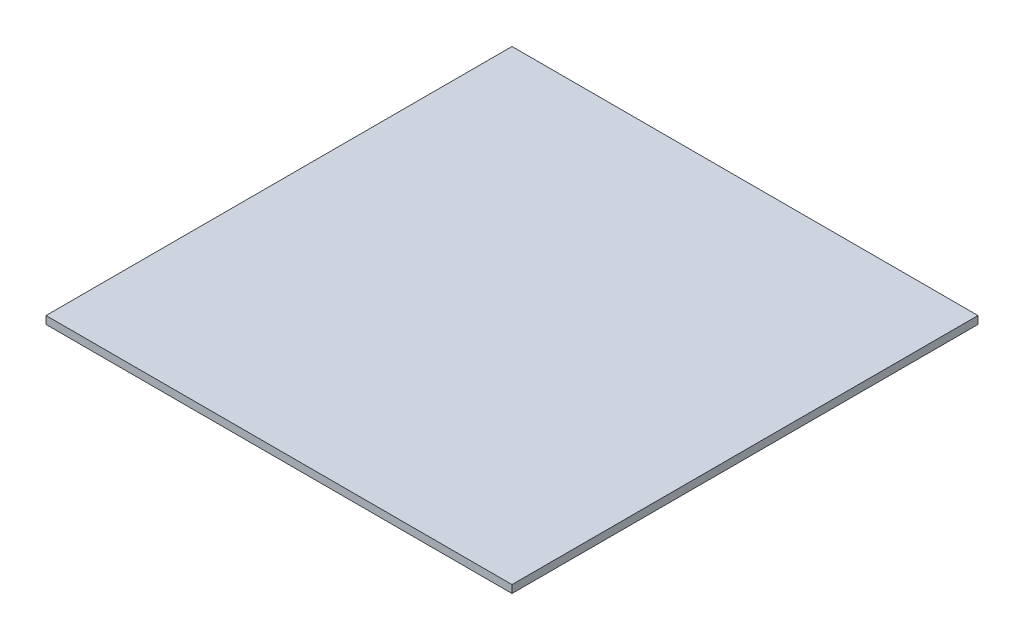
SolidWorks part; units mm, degrees
ref_plane "Front Plane" through (0, 0, 0) normal (0, 0, 1) x (1, 0, 0)
ref_plane "Top Plane" through (0, 0, 0) normal (0, 1, 0) x (1, 0, 0)
ref_plane "Right Plane" through (0, 0, 0) normal (1, 0, 0) x (0, 0, -1)
sketch "Sketch1" plane through (0, 0, 0) normal (0, 1, 0) x (1, 0, 0)
  line L1 (-152.4, -152.4) -> (152.4, -152.4)
  line L2 (-152.4, -152.4) -> (-152.4, 152.4)
  line L3 (-152.4, 152.4) -> (152.4, 152.4)
  line L4 (152.4, -152.4) -> (152.4, 152.4)
  line L5 (-152.4, -152.4) -> (152.4, 152.4) construction
  line L6 (-152.4, 152.4) -> (152.4, -152.4) construction
  point P0 (0, 0)
  dimension "D1" = 304.8
  dimension "D2" = 304.8
extrude "Boss-Extrude1" add sketch "Sketch1" along normal blind 5.08
